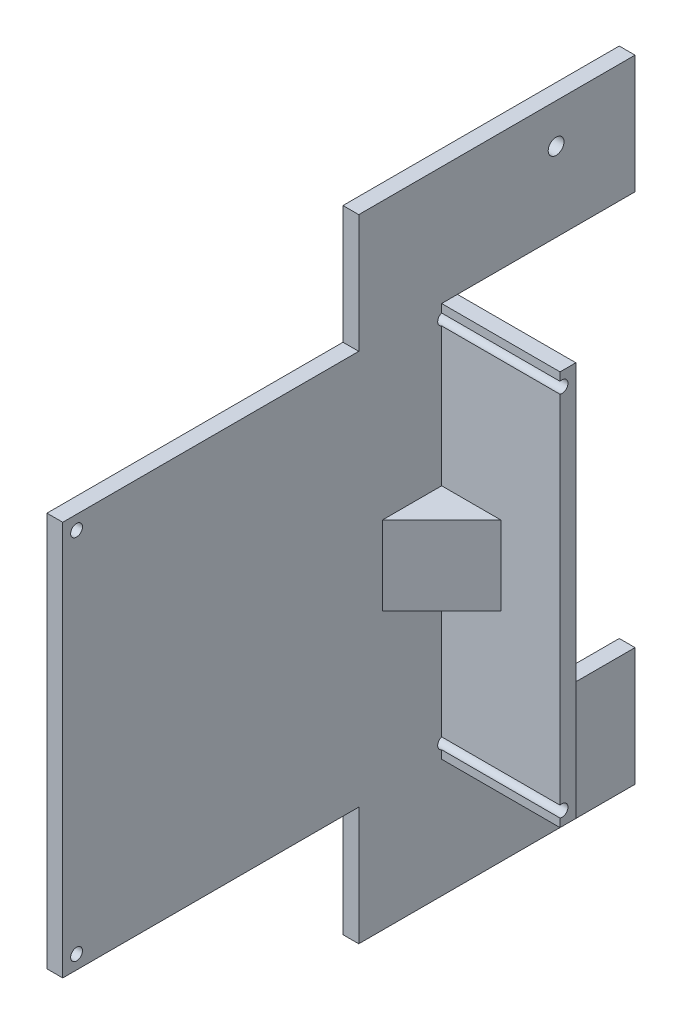
SolidWorks part; units mm, degrees
ref_plane "前视基准面" through (0, 0, 0) normal (0, 0, 1) x (1, 0, 0)
ref_plane "上视基准面" through (0, 0, 0) normal (0, 1, 0) x (1, 0, 0)
ref_plane "右视基准面" through (0, 0, 0) normal (1, 0, 0) x (0, 0, -1)
other "Configuration Table"
sketch "草图1" plane through (0, 0, 0) normal (1, 0, 0) x (0, 0, -1)
  line L1 (-50, 50) -> (50, 50)
  line L2 (-50, 50) -> (-50, -50)
  line L3 (-50, -50) -> (50, -50)
  line L4 (50, 50) -> (50, -50)
  dimension "D1" = 100
  dimension "D2" = 50
  dimension "D3" = 50
extrude "凸台-拉伸1" add sketch "草图1" along normal blind 4
sketch "草图2" plane through (4, 0, 0) normal (1, 0, 0) x (0, 0, -1)
  line L0 (-50, -50) -> (50, -50) construction
  line L1 (50, 50) -> (46, 50)
  line L2 (50, 50) -> (50, -50)
  line L3 (50, -50) -> (46, -50)
  line L4 (46, 50) -> (46, -50)
  dimension "D1" = 4
extrude "凸台-拉伸2" add sketch "草图2" along normal blind 30
sketch "草图3" plane through (0, 0, 0) normal (-1, 0, 0) x (0, 0, 1)
  line L0 (-50, 50) -> (50, 50) construction
  line L1 (-25, 50) -> (-95, 50)
  line L2 (-25, 50) -> (-25, 80)
  line L3 (-25, 80) -> (-95, 80)
  line L4 (-95, 50) -> (-95, 80)
  line L5 (50, -50) -> (-50, -50) construction
  line L6 (-25, -50) -> (-95, -50)
  line L7 (-25, -50) -> (-25, -80)
  line L8 (-25, -80) -> (-95, -80)
  line L9 (-95, -50) -> (-95, -80)
  line L10 (-50, -50) -> (-50, 50) construction
  dimension "D1" = 30
  dimension "D2" = 30
  dimension "D3" = 25
  dimension "D4" = 25
  dimension "D5" = 45
  dimension "D6" = 45
extrude "凸台-拉伸3" add sketch "草图3" against normal blind 4
sketch "草图4" plane through (4, 0, 0) normal (1, 0, 0) x (0, 0, -1)
  line L0 (95, -80) -> (25, -80) construction
  line L1 (95, 80) -> (95, 50) construction
  circle A0 centre (75, 70) radius 2
  circle A1 centre (75, -70) radius 2
  point P8 (0, 0)
  dimension "D1" = 140
  dimension "D3" = 4
  dimension "D4" = 4
  dimension "D2" = 10
  dimension "D5" = 20
extrude "切除-拉伸1" cut sketch "草图4" against normal through all
sketch "草图5" plane through (0, 0, 0) normal (-1, 0, 0) x (0, 0, 1)
  line L1 (-46.5, 46.5) -> (46.5, 46.5) construction
  line L2 (-46.5, 46.5) -> (-46.5, -46.5) construction
  line L3 (-46.5, -46.5) -> (46.5, -46.5) construction
  line L4 (46.5, 46.5) -> (46.5, -46.5) construction
  circle A0 centre (46.5, 46.5) radius 1.5
  circle A1 centre (-46.5, 46.5) radius 1.5
  circle A2 centre (-46.5, -46.5) radius 1.5
  circle A3 centre (46.5, -46.5) radius 1.5
  dimension "D4" = 3
  dimension "D1" = 93
  dimension "D2" = 46.5
  dimension "D3" = 46.5
extrude "切除-拉伸2" cut sketch "草图5" against normal through all
sketch "草图6" plane through (0, 0, 0) normal (0, 1, 0) x (1, 0, 0)
  line L0 (4, 31) -> (19, 46)
  line L1 (4, 25) -> (4, 95) construction
  line L2 (34, 46) -> (4, 46) construction
  line L3 (19, 46) -> (4, 46)
  line L4 (4, 46) -> (4, 31)
  dimension "D1" = 15
  dimension "D2" = 15
extrude "凸台-拉伸4" add sketch "草图6" along normal blind 10 and the other way blind 10
